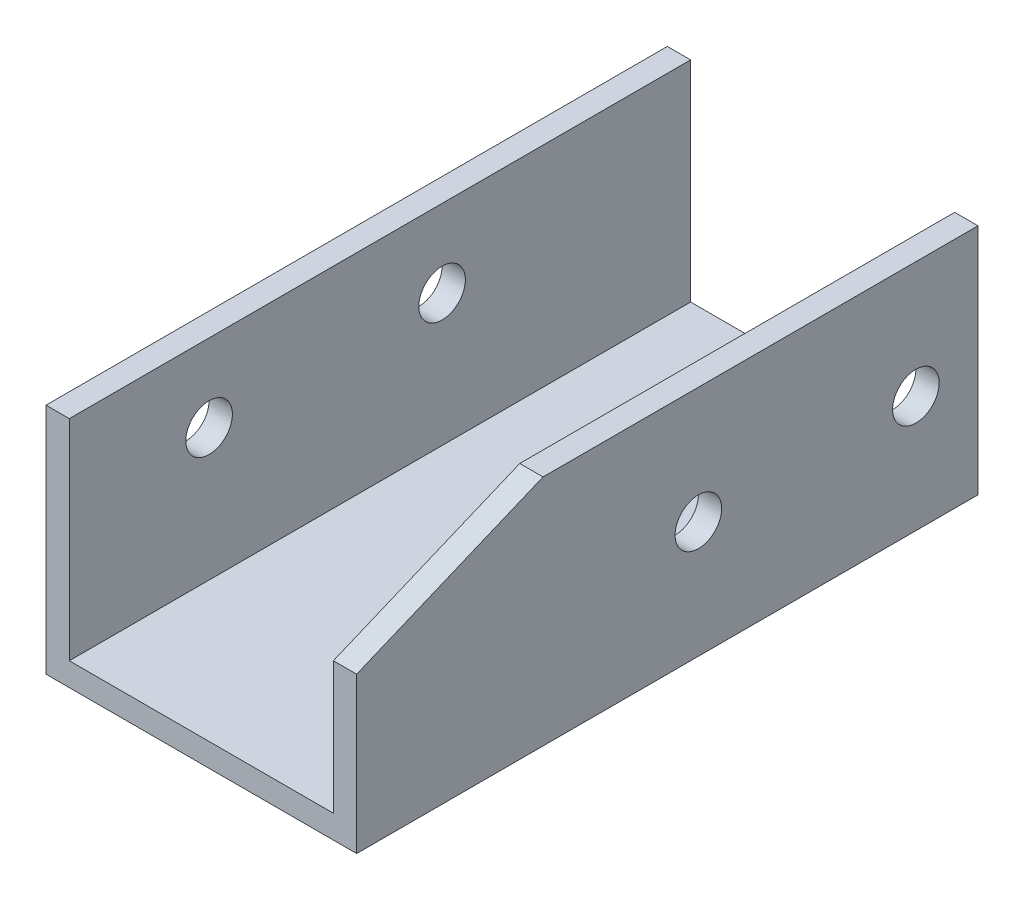
SolidWorks part; units mm, degrees
ref_plane "Plan de face" through (0, 0, 0) normal (0, 0, 1) x (1, 0, 0)
ref_plane "Plan de dessus" through (0, 0, 0) normal (0, 1, 0) x (1, 0, 0)
ref_plane "Plan de droite" through (0, 0, 0) normal (1, 0, 0) x (0, 0, -1)
sketch "Esquisse1" plane through (0, 0, 0) normal (0, 0, 1) x (1, 0, 0)
  line L0 (-17.0908, 12.954) -> (-17.0908, -2.046)
  line L1 (-17.0908, -2.046) -> (2.9092, -2.046)
  line L2 (2.9092, -2.046) -> (2.9092, 12.954)
  line L3 (2.9092, 12.954) -> (1.4092, 12.954)
  line L4 (1.4092, 12.954) -> (1.4092, -0.546)
  line L5 (1.4092, -0.546) -> (-15.5908, -0.546)
  line L6 (-15.5908, -0.546) -> (-15.5908, 12.954)
  line L7 (-15.5908, 12.954) -> (-17.0908, 12.954)
  dimension "D1" = 1.5
  dimension "D2" = 1.5
  dimension "D3" = 1.5
  dimension "D4" = 15
  dimension "D5" = 15
  dimension "D6" = 20
extrude "Extrusion1" add sketch "Esquisse1" along normal blind 40
sketch "Esquisse2" plane through (2.9092, 0, 0) normal (1, 0, 0) x (0, 0, -1)
  line L0 (-18, 5.454) -> (-4, 5.454) construction
  line L1 (-40, -2.046) -> (-40, 12.954) construction
  line L2 (0, -2.046) -> (0, 12.954) construction
  line L3 (-40, -2.046) -> (0, -2.046) construction
  line L4 (-40, 12.954) -> (-28, 12.954)
  line L5 (-40, 12.954) -> (0, 12.954) construction
  line L6 (-28, 12.954) -> (-40, 7.954)
  line L7 (-40, 7.954) -> (-40, 12.954)
  circle A0 centre (-18, 5.454) radius 1.5
  circle A1 centre (-4, 5.454) radius 1.5
  dimension "D1" = 4
  dimension "D2" = 14
  dimension "D3" = 7.5
  dimension "D4" = 12
  dimension "D5" = 5
extrude "Extrusion2" cut sketch "Esquisse2" against normal blind 10
sketch "Esquisse6" plane through (-17.0908, 0, 0) normal (-1, 0, 0) x (0, 0, 1)
  line L0 (16, 7.954) -> (31, 7.954) construction
  line L1 (0, 12.954) -> (0, -2.046) construction
  line L2 (40, -2.046) -> (0, -2.046) construction
  line L3 (40, 12.954) -> (40, -2.046) construction
  circle A0 centre (31, 7.954) radius 1.5
  circle A1 centre (16, 7.954) radius 1.5
  point P4 (0, 5.454)
  point P7 (20, -2.046)
  dimension "D1" = 9
  dimension "D2" = 16
  dimension "D3" = 10
extrude "Extrusion6" cut sketch "Esquisse6" against normal blind 10
